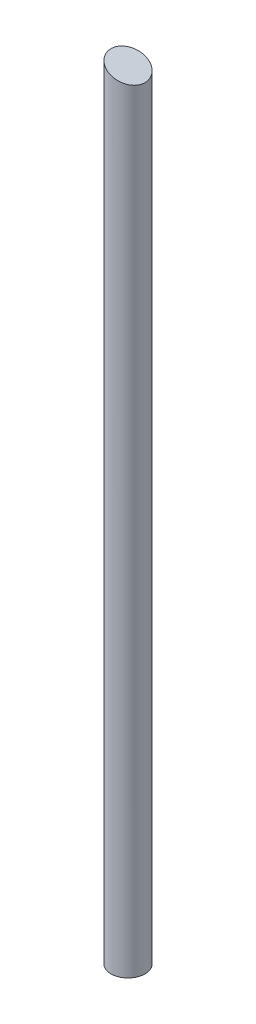
SolidWorks part; units mm, degrees
ref_plane "前基準面" through (0, 0, 0) normal (0, 0, 1) x (1, 0, 0)
ref_plane "上基準面" through (0, 0, 0) normal (0, 1, 0) x (1, 0, 0)
ref_plane "右基準面" through (0, 0, 0) normal (1, 0, 0) x (0, 0, -1)
sketch "草圖1" plane through (0, 0, 0) normal (0, 1, 0) x (1, 0, 0)
  circle A0 centre (0, 0) radius 3
  dimension "D1" = 6
extrude "填料-伸長1" add sketch "草圖1" along normal blind 138
ref_plane "平面1" through (0, 120, 0) normal (0, 1, 0) x (1, 0, 0)
sketch "草圖3" plane through (0, 0, 0) normal (0, 0, 1) x (1, 0, 0)
  line L0 (-3, 138) -> (3, 135.8162)
  line L1 (3, 138) -> (-3, 138) construction
  line L2 (-3, 138) -> (3, 138)
  line L3 (3, 138) -> (3, 135.8162)
  dimension "D1" = 20
extrude "除料-伸長2" cut sketch "草圖3" against normal mid plane 10
